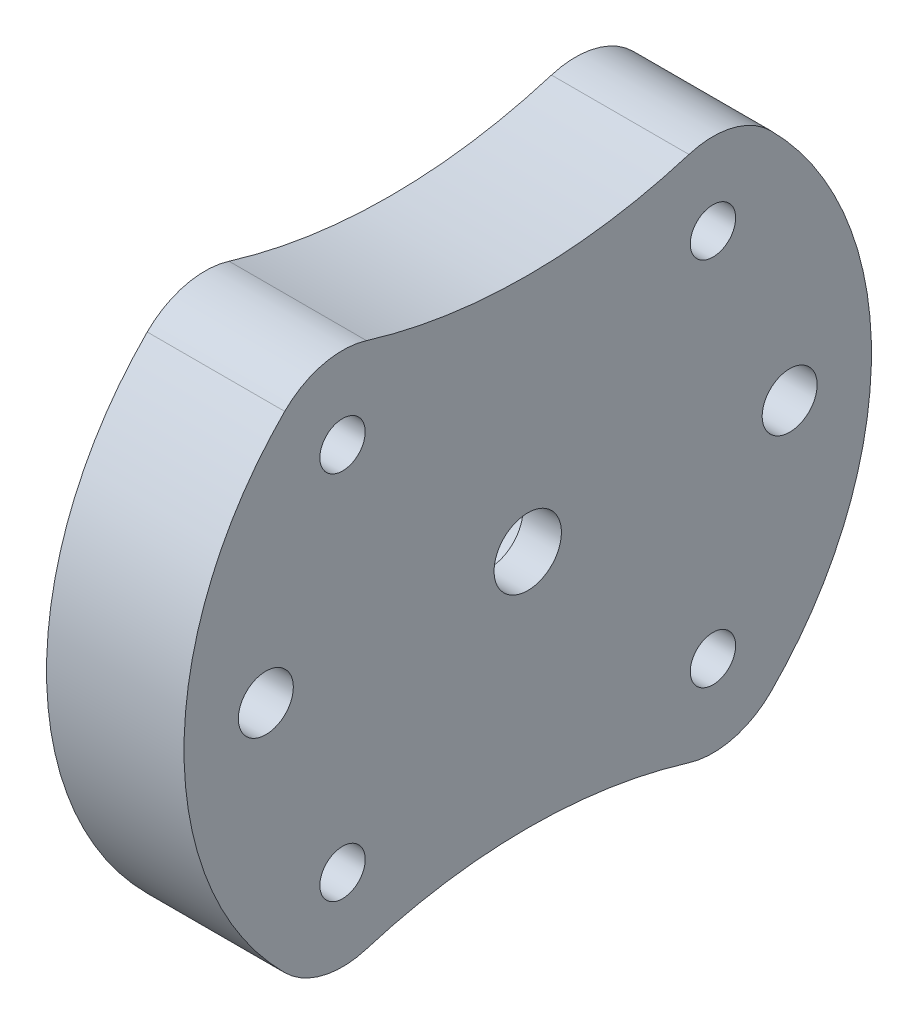
SolidWorks part; units mm, degrees
ref_plane "正面" through (0, 0, 0) normal (0, 0, 1) x (1, 0, 0)
ref_plane "平面" through (0, 0, 0) normal (0, 1, 0) x (1, 0, 0)
ref_plane "右側面" through (0, 0, 0) normal (1, 0, 0) x (0, 0, -1)
sketch "ｽｹｯﾁ1" plane through (0, 0, 0) normal (1, 0, 0) x (0, 0, -1)
  circle A0 centre (0, 0) radius 25
  dimension "D1" = 50
extrude "ﾎﾞｽ - 押し出し1" add sketch "ｽｹｯﾁ1" along normal blind 10
sketch "ｽｹｯﾁ3" plane through (10, 0, 0) normal (1, 0, 0) x (0, 0, -1)
  circle A0 centre (0, 0) radius 2.45
  dimension "D1" = 4.9
extrude "ｶｯﾄ - 押し出し1" cut sketch "ｽｹｯﾁ3" against normal through all
sketch "ｽｹｯﾁ5" plane through (0, 0, 0) normal (-1, 0, 0) x (0, 0, 1)
  circle A0 centre (0, 0) radius 4.95
  dimension "D1" = 9.9
extrude "ｶｯﾄ - 押し出し2" cut sketch "ｽｹｯﾁ5" against normal blind 7.2
sketch "ｽｹｯﾁ6" plane through (10, 0, 0) normal (1, 0, 0) x (0, 0, -1)
  line L0 (0, 0) -> (0, 25) construction
  line L1 (0, 0) -> (-19.05, 0) construction
  circle A0 centre (0, 0) radius 25 construction
  circle A1 centre (-19.05, 0) radius 2
  circle A2 centre (19.05, 0) radius 2
  dimension "D1" = 4
  dimension "D2" = 38.1
extrude "ｶｯﾄ - 押し出し3" cut sketch "ｽｹｯﾁ6" against normal through all
sketch "ｽｹｯﾁ7" plane through (10, 0, 0) normal (1, 0, 0) x (0, 0, -1)
  line L1 (-13.4704, 13.4704) -> (13.4704, 13.4704) construction
  line L2 (-13.4704, 13.4704) -> (-13.4704, -13.4704) construction
  line L3 (-13.4704, -13.4704) -> (13.4704, -13.4704) construction
  line L4 (13.4704, 13.4704) -> (13.4704, -13.4704) construction
  line L5 (-13.4704, 13.4704) -> (13.4704, -13.4704) construction
  line L6 (-13.4704, -13.4704) -> (13.4704, 13.4704) construction
  circle A0 centre (13.4704, 13.4704) radius 1.65
  circle A1 centre (13.4704, -13.4704) radius 1.65
  circle A2 centre (-13.4704, -13.4704) radius 1.65
  circle A3 centre (-13.4704, 13.4704) radius 1.65
  point P0 (0, 0)
  dimension "D2" = 3.3
  dimension "D1" = 38.1
  dimension "D3" = 4
extrude "ｶｯﾄ - 押し出し4" cut sketch "ｽｹｯﾁ7" against normal through all
sketch "ｽｹｯﾁ8" plane through (10, 0, 0) normal (1, 0, 0) x (0, 0, -1)
  line L0 (0, 0) -> (0, 57.4016) construction
  line L1 (0, 0) -> (25, 0) construction
  circle A0 centre (-13.4704, 13.4704) radius 5.95
  circle A1 centre (0, 0) radius 2.45
  circle A2 centre (0, 0) radius 2.45
  circle A3 centre (19.05, 0) radius 2
  circle A4 centre (19.05, 0) radius 2
  circle A5 centre (-19.05, 0) radius 2
  circle A6 centre (-19.05, 0) radius 2
  circle A7 centre (13.4704, 13.4704) radius 1.65
  circle A8 centre (13.4704, 13.4704) radius 1.65
  circle A9 centre (13.4704, -13.4704) radius 1.65
  circle A10 centre (13.4704, -13.4704) radius 1.65
  circle A11 centre (-13.4704, -13.4704) radius 1.65
  circle A12 centre (-13.4704, -13.4704) radius 1.65
  circle A13 centre (-13.4704, 13.4704) radius 1.65
  circle A14 centre (-13.4704, 13.4704) radius 1.65
  circle A15 centre (0, 0) radius 25
  circle A16 centre (0, 0) radius 25
  circle A17 centre (13.4704, 13.4704) radius 5.95
  circle A18 centre (13.4704, -13.4704) radius 5.95
  circle A19 centre (-13.4704, -13.4704) radius 5.95
  circle A20 centre (0, 57.4016) radius 40
  circle A21 centre (0, -57.4016) radius 40
  circle M18 centre (0, 0) radius 25
  dimension "D9" = 80
  dimension "D1" = 0
  dimension "D2" = 0
  dimension "D3" = 0
  dimension "D4" = 0
  dimension "D5" = 0
  dimension "D6" = 0
  dimension "D7" = 0
  dimension "D8" = 0
extrude "ｶｯﾄ - 押し出し5" cut sketch "ｽｹｯﾁ8" against normal through all contours A21 M18 | A20 M18 | A20 A16 A0 | A20 A17 A16 | A16 A21 A19 | A18 A21 A16
